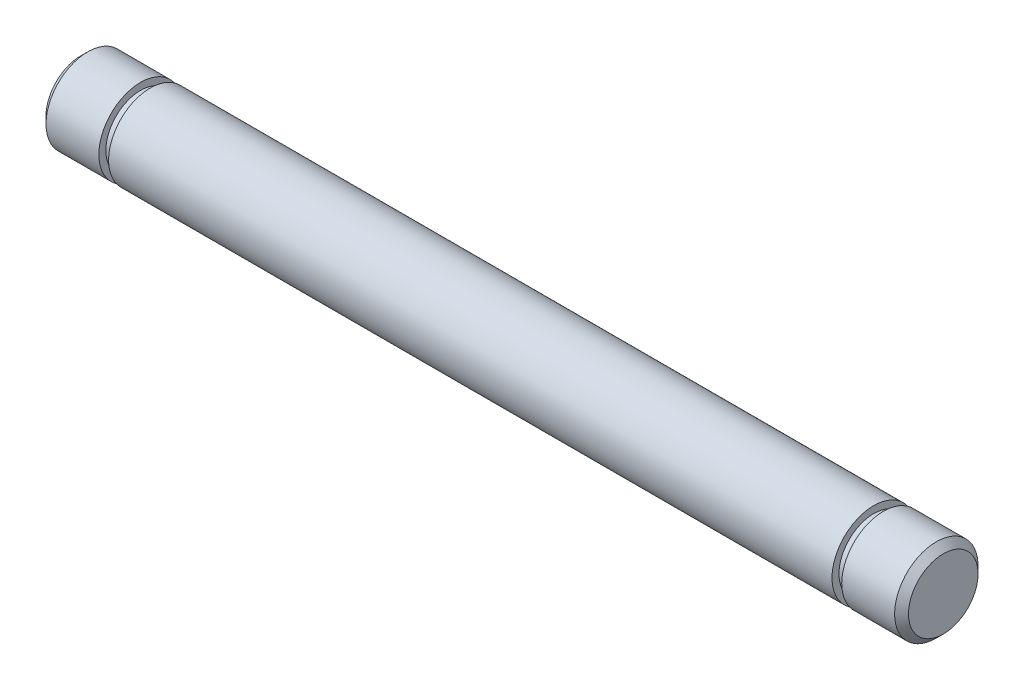
SolidWorks part; units mm, degrees
ref_plane "正面" through (0, 0, 0) normal (0, 0, 1) x (1, 0, 0)
ref_plane "平面" through (0, 0, 0) normal (0, 1, 0) x (1, 0, 0)
ref_plane "右側面" through (0, 0, 0) normal (1, 0, 0) x (0, 0, -1)
ref_plane "平面1" through (0, 0, 0) normal (0, 0, 1) x (1, 0, 0)
sketch "ｽｹｯﾁ1" plane through (0, 0, 0) normal (0, 0, 1) x (1, 0, 0)
  line L0 (0, 0) -> (0, 2.5)
  line L1 (0, 2.5) -> (0.5, 3)
  line L2 (0.5, 3) -> (61.5, 3)
  line L3 (61.5, 3) -> (62, 2.5)
  line L4 (62, 2.5) -> (62, 0)
  line L5 (62, 0) -> (0, 0)
  line L6 (62, 0) -> (0, 0) construction
revolve "回転1" add sketch "ｽｹｯﾁ1" angle 360 about L6
ref_plane "平面2" through (5, 0, 0) normal (1, 0, 0) x (0, 0, -1)
sketch "ｽｹｯﾁ2" plane through (5, 0, 0) normal (1, 0, 0) x (0, 0, -1)
  circle A0 centre (0, 0) radius 6
  circle A1 centre (0, 0) radius 2.5
extrude "ｶｯﾄ - 押し出し1" cut sketch "ｽｹｯﾁ2" against normal blind 0.7
ref_plane "平面3" through (57, 0, 0) normal (1, 0, 0) x (0, 0, -1)
sketch "ｽｹｯﾁ3" plane through (57, 0, 0) normal (1, 0, 0) x (0, 0, -1)
  circle A0 centre (0, 0) radius 6
  circle A1 centre (0, 0) radius 2.5
extrude "ｶｯﾄ - 押し出し2" cut sketch "ｽｹｯﾁ3" along normal blind 0.7
